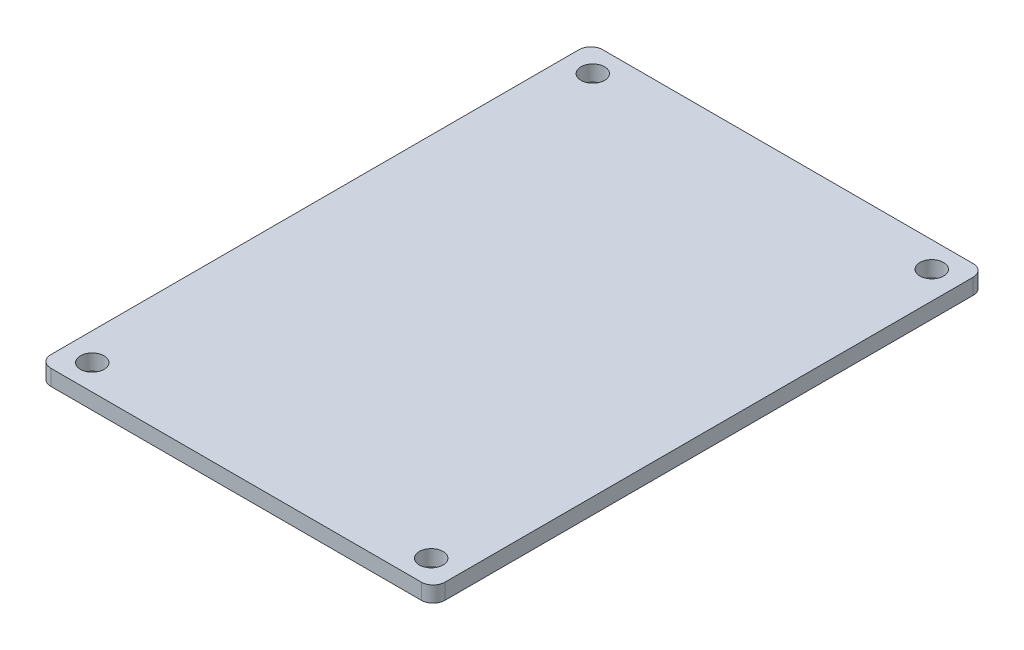
SolidWorks part; units mm, degrees
ref_plane "Front Plane" through (0, 0, 0) normal (0, 0, 1) x (1, 0, 0)
ref_plane "Top Plane" through (0, 0, 0) normal (0, 1, 0) x (1, 0, 0)
ref_plane "Right Plane" through (0, 0, 0) normal (1, 0, 0) x (0, 0, -1)
sketch "Sketch1" plane through (0, 0, 0) normal (0, 1, 0) x (1, 0, 0)
  line L1 (-67.2101, 82.808) -> (32.7899, 82.808)
  line L2 (-67.2101, 82.808) -> (-67.2101, -57.192)
  line L3 (-67.2101, -57.192) -> (32.7899, -57.192)
  line L4 (32.7899, 82.808) -> (32.7899, -57.192)
  dimension "D1" = 100
  dimension "D2" = 140
extrude "Boss-Extrude1" add sketch "Sketch1" along normal blind 4
sketch "Sketch2" plane through (0, 4, 0) normal (0, 1, 0) x (1, 0, 0)
  line L0 (32.7899, -57.192) -> (32.7899, 82.808) construction
  line L1 (-67.2101, -57.192) -> (32.7899, -57.192) construction
  line L2 (32.7899, 82.808) -> (-67.2101, 82.808) construction
  line L3 (-67.2101, 82.808) -> (-67.2101, -57.192) construction
  circle A0 centre (25.7899, -50.692) radius 3
  circle A1 centre (-60.2101, -50.692) radius 3
  circle A2 centre (25.7899, 76.308) radius 3
  circle A3 centre (-60.2101, 76.308) radius 3
  point P2 (-3.3008, -5.2202)
  point P3 (22.0872, -47.0834)
  point P10 (-60.6938, -51.192)
  point P13 (26.2899, 77.966)
  point P16 (-60.6938, 77.966)
  dimension "D1" = 7
  dimension "D2" = 6
  dimension "D4" = 6.5
  dimension "D10" = 6
  dimension "D11" = 6
  dimension "D12" = 6
  dimension "D3" = 6.5
  dimension "D5" = 7
  dimension "D6" = 6.5
  dimension "D7" = 7
  dimension "D8" = 7
  dimension "D9" = 6.5
extrude "Cut-Extrude1" cut sketch "Sketch2" against normal blind 4
fillet "Fillet1" radius 3 4 edges at (32.7899, 2, 57.192) (32.7899, 2, -82.808) (-67.2101, 2, -82.808) (-67.2101, 2, 57.192)
